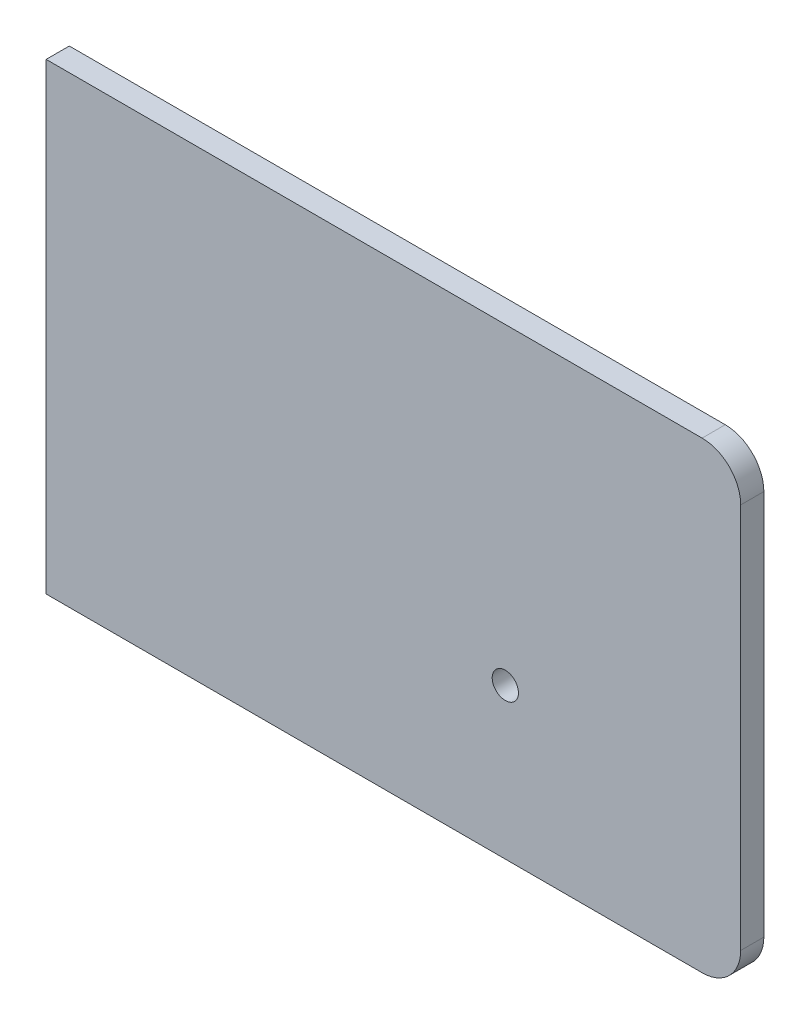
SolidWorks part; units mm, degrees
ref_plane "Front Plane" through (0, 0, 0) normal (0, 0, 1) x (1, 0, 0)
ref_plane "Top Plane" through (0, 0, 0) normal (0, 1, 0) x (1, 0, 0)
ref_plane "Right Plane" through (0, 0, 0) normal (1, 0, 0) x (0, 0, -1)
sketch "Sketch2" plane through (0, 0, 0) normal (0, 0, 1) x (1, 0, 0)
  line L5 (22.6774, 408.3286) -> (202.6774, 408.3286)
  line L6 (22.6774, 408.3286) -> (22.6774, 288.3286)
  line L7 (22.6774, 288.3286) -> (202.6774, 288.3286)
  line L17 (202.6774, 408.3286) -> (202.6774, 288.3286)
  circle A17 centre (141.6774, 327.3286) radius 3.4
  dimension "D4" = 81
  dimension "D3" = 6.8
  dimension "D1" = 180
  dimension "D2" = 120
  dimension "D5" = 61
extrude "Boss-Extrude1" add sketch "Sketch2" along normal blind 6
fillet "Fillet1" radius 10 2 edges at (202.6774, 288.3286, 3) (202.6774, 408.3286, 3)
